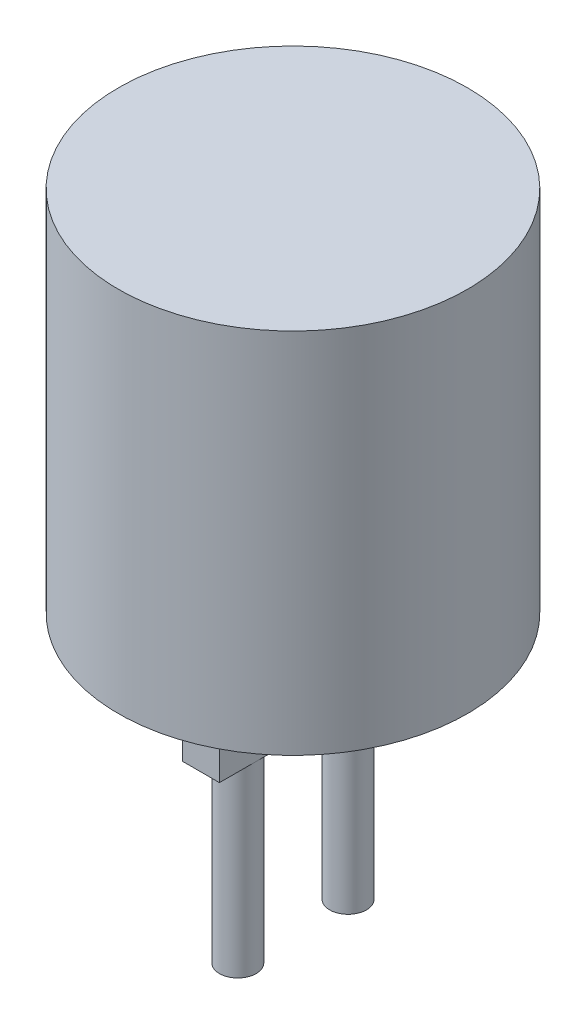
SolidWorks part; units mm, degrees
material "PS Среднего/Высокого потока"
ref_plane "Спереди" through (0, 0, 0) normal (0, 0, 1) x (1, 0, 0)
ref_plane "Сверху" through (0, 0, 0) normal (0, 1, 0) x (1, 0, 0)
ref_plane "Справа" through (0, 0, 0) normal (1, 0, 0) x (0, 0, -1)
sketch "Эскиз1" plane through (0, 0, 0) normal (0, 0, 1) x (1, 0, 0)
  line L0 (0, 0) -> (0, 100.9265) construction
  line L1 (0, 0) -> (9.5, 0)
  line L2 (9.5, 0) -> (9.5, 20)
  line L3 (9.5, 20) -> (0, 20)
  line L4 (0, 20) -> (0, 0)
  dimension "D4" = 20
  dimension "D1" = 9.5
revolve "Корпус заряда" add sketch "Эскиз1" angle 360 about L0
sketch "Эскиз2" plane through (0, 0, 0) normal (0, 1, 0) x (1, 0, 0)
  line L0 (0, 0) -> (0, -7.3775) construction
  circle A0 centre (0, -3) radius 1
  circle A1 centre (0, 3) radius 1
  dimension "D1" = 2
  dimension "D2" = 2
  dimension "D3" = 3
  dimension "D4" = 3
extrude "Контакты" add sketch "Эскиз2" against normal blind 15
sketch "Эскиз3" plane through (0, 0, 0) normal (0, 1, 0) x (1, 0, 0)
  line L1 (-1, 5) -> (1, 5)
  line L2 (-1, 5) -> (-1, -5)
  line L3 (-1, -5) -> (1, -5)
  line L4 (1, 5) -> (1, -5)
  line L5 (-1, 5) -> (1, -5) construction
  line L6 (-1, -5) -> (1, 5) construction
  point P0 (0, 0)
  dimension "D1" = 2
  dimension "D2" = 10
extrude "Разъём" add sketch "Эскиз3" against normal blind 5
